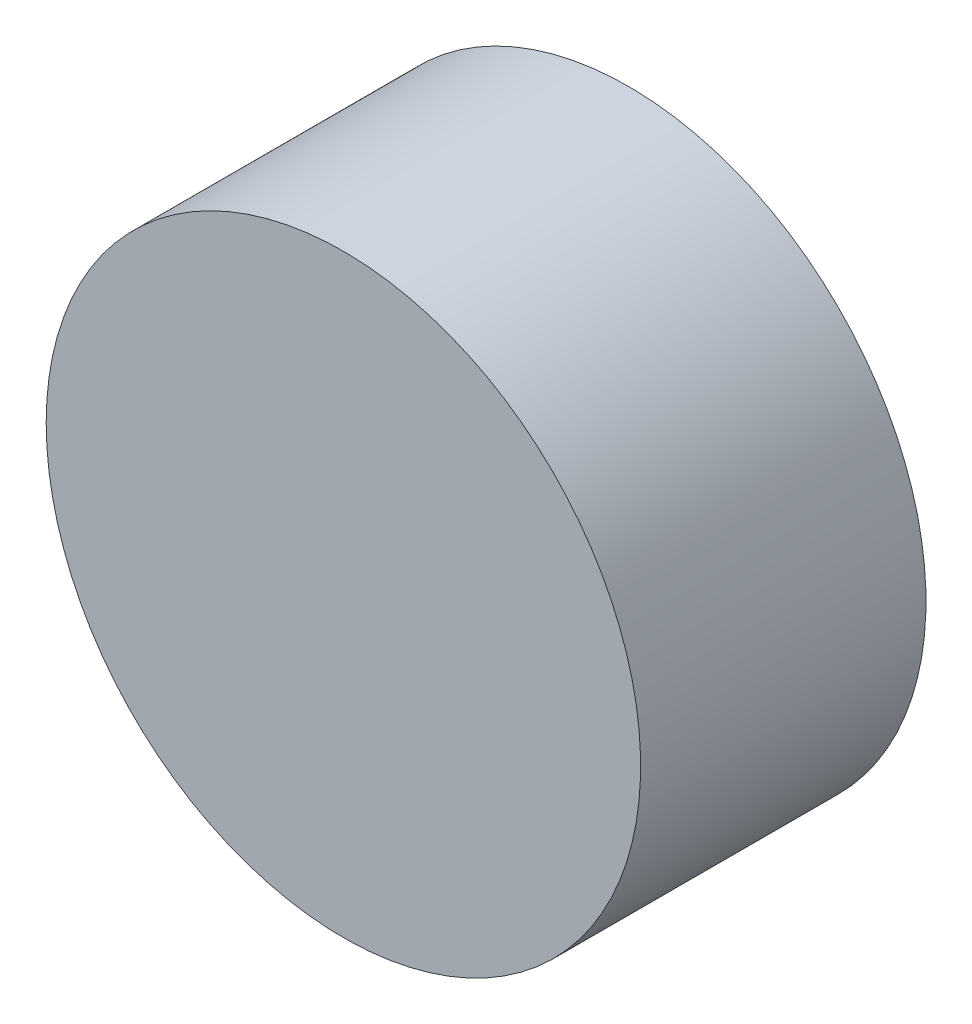
SolidWorks part; units mm, degrees
ref_plane "Front Plane" through (0, 0, 0) normal (0, 0, 1) x (1, 0, 0)
ref_plane "Top Plane" through (0, 0, 0) normal (0, 1, 0) x (1, 0, 0)
ref_plane "Right Plane" through (0, 0, 0) normal (1, 0, 0) x (0, 0, -1)
sketch "Sketch1" plane through (0, 0, 0) normal (0, 0, 1) x (1, 0, 0)
  circle A0 centre (0, 0) radius 1.5875
  dimension "D1" = 3.175
extrude "Boss-Extrude1" add sketch "Sketch1" along normal blind 1.524
